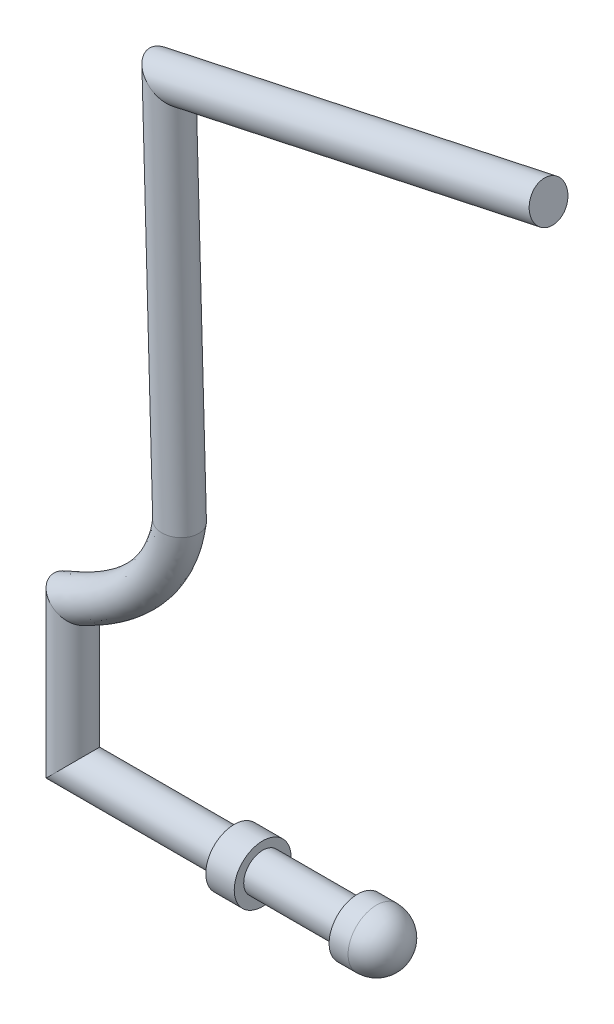
SolidWorks part; units mm, degrees
ref_plane "Front Plane" through (0, 0, 0) normal (0, 0, 1) x (1, 0, 0)
ref_plane "Top Plane" through (0, 0, 0) normal (0, 1, 0) x (1, 0, 0)
ref_plane "Right Plane" through (0, 0, 0) normal (1, 0, 0) x (0, 0, -1)
sketch "Sketch23" plane through (0, 0, 0) normal (0, 0, 1) x (1, 0, 0)
  line L0 (23.0702, 32.6631) -> (-16.9298, 24.0547)
  line L1 (-16.9298, 24.0547) -> (-15.8158, -15.9453)
  line L2 (-27.0574, -28.6048) -> (-27.0574, -43.6048)
  line L3 (-27.0574, -43.6048) -> (2.9426, -43.6048)
  spline S0 degree 2 poles (-15.8158, -15.9453) (-17.1089, -24.2398) (-27.0574, -28.6048) knots 0 0 0 1 1 1
  point P6 (-15.8231, -15.6728)
  dimension "D1" = 40
  dimension "D2" = 40
  dimension "D3" = 15
  dimension "D4" = 30
sweep "Sweep2" add path "Sketch23" circular profile diameter 4 parameters "D3"=4
sketch "Sketch33" plane through (2.9426, 0, 0) normal (1, 0, 0) x (0, 0, -1)
  circle A0 centre (0, -43.6048) radius 3
  dimension "D1" = 6
extrude "Boss-Extrude1" add sketch "Sketch33" along normal blind 5
fillet "Fillet1" radius 3 1 edges at (7.9426, -43.6048, -3)
sketch "Sketch35" plane through (2.9426, 0, 0) normal (-1, 0, 0) x (0, 0, 1)
  circle A0 centre (0, -43.7413) radius 3
  dimension "D1" = 6
extrude "Boss-Extrude2" add sketch "Sketch35" along normal blind 3 from offset 10
